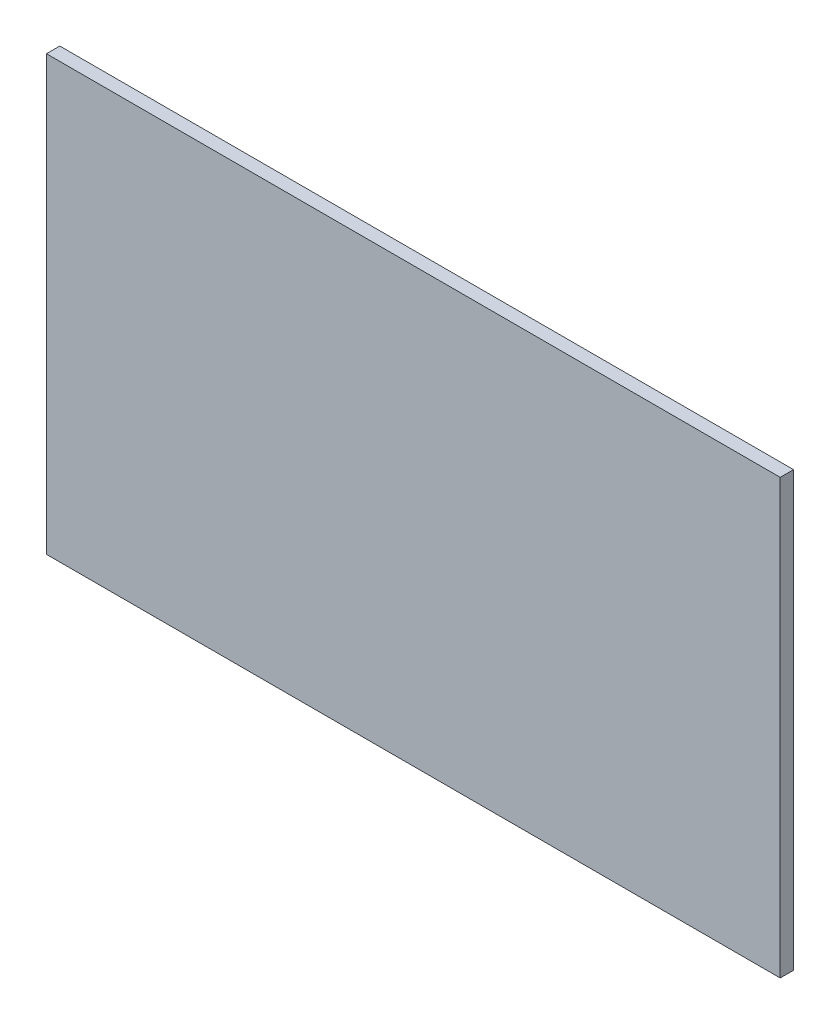
SolidWorks part; units mm, degrees
material "Сосна"
ref_plane "Спереди" through (0, 0, 0) normal (0, 0, 1) x (1, 0, 0)
ref_plane "Сверху" through (0, 0, 0) normal (0, 1, 0) x (1, 0, 0)
ref_plane "Справа" through (0, 0, 0) normal (1, 0, 0) x (0, 0, -1)
sketch "Эскиз1" plane through (0, 0, 0) normal (0, 0, 1) x (1, 0, 0)
  line L1 (-753.0225, 717.962) -> (1446.9775, 717.962)
  line L2 (-753.0225, 717.962) -> (-753.0225, -582.038)
  line L3 (-753.0225, -582.038) -> (1446.9775, -582.038)
  line L4 (1446.9775, 717.962) -> (1446.9775, -582.038)
  dimension "D1" = 2200
  dimension "D2" = 1300
extrude "Бобышка-Вытянуть1" add sketch "Эскиз1" along normal blind 40
